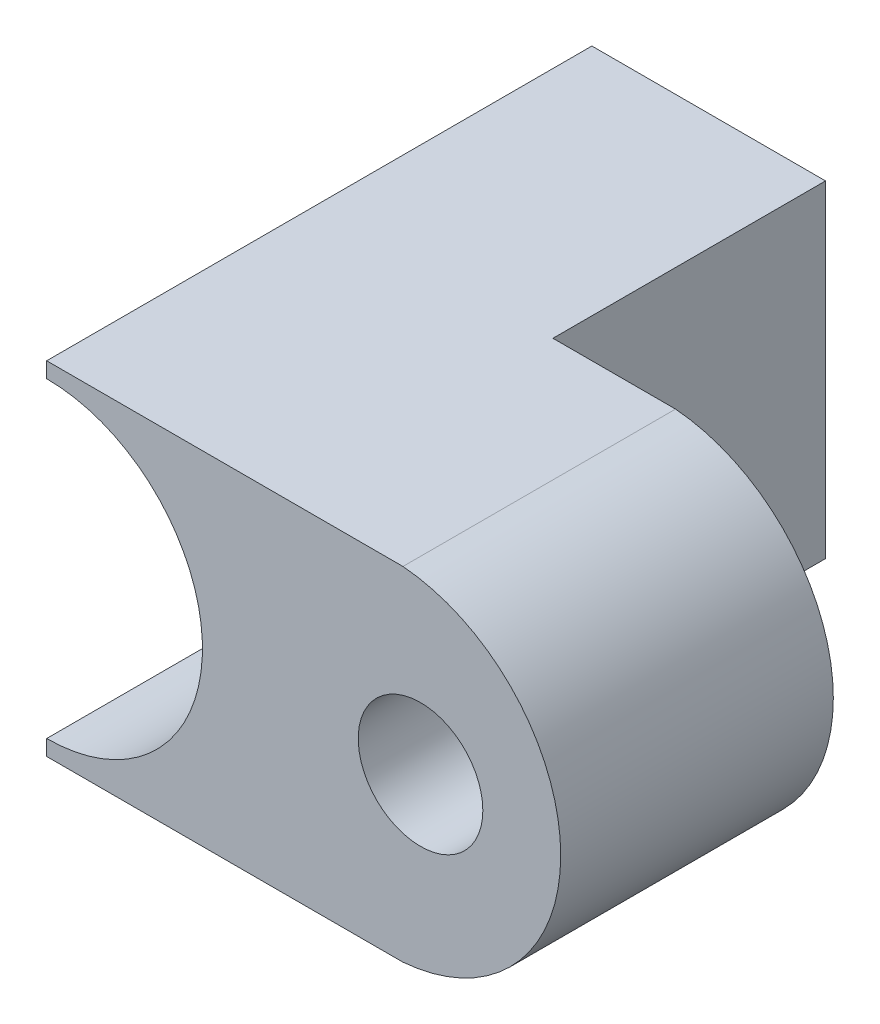
SolidWorks part; units mm, degrees
material "AISI Type A2 Tool Steel Custom"
ref_plane "Front Plane" through (0, 0, 0) normal (0, 0, 1) x (1, 0, 0)
ref_plane "Top Plane" through (0, 0, 0) normal (0, 1, 0) x (1, 0, 0)
ref_plane "Right Plane" through (0, 0, 0) normal (1, 0, 0) x (0, 0, -1)
sketch "Sketch1" plane through (0, 0, 0) normal (0, 0, 1) x (1, 0, 0)
  line L1 (0, -1.27) -> (29.0467, -1.27)
  line L3 (0, 26.67) -> (29.0467, 26.67)
  line L9 (0, 25.4) -> (0, 26.67)
  line L10 (0, 0) -> (0, -1.27)
  arc A1 (0, 0) -> (0, 25.4) centre (0, 12.7) ccw
  arc A4 (29.0467, -1.27) -> (29.0467, 26.67) centre (27.8924, 12.7) ccw
  point P3 (41.91, 12.7)
  dimension "D2" = 25.4
  dimension "D5" = 14.0176
  dimension "D3" = 41.91
  dimension "D1" = 1.27
  dimension "D4" = 1.27
extrude "Boss-Extrude1" add sketch "Sketch1" along normal blind 44.45
sketch "Sketch2" plane through (0, 0, 0) normal (0, 0, -1) x (-1, 0, 0)
  line L0 (-19.05, -1.27) -> (-19.05, 26.67)
  line L1 (0, -1.27) -> (-29.0467, -1.27) construction
  line L2 (-29.0467, 26.67) -> (0, 26.67) construction
  line L3 (0, -1.27) -> (-29.0467, -1.27) construction
  line L4 (-29.0467, 26.67) -> (0, 26.67) construction
  line L5 (-19.05, -1.27) -> (-29.0467, -1.27)
  line L10 (-29.0467, 26.67) -> (-19.05, 26.67)
  arc A1 (-29.0467, 26.67) -> (-29.0467, -1.27) centre (-27.8924, 12.7) ccw construction
  arc A3 (-29.0467, 26.67) -> (-29.0467, -1.27) centre (-27.8924, 12.7) ccw
  dimension "D1" = 19.05
extrude "Cut-Extrude1" cut sketch "Sketch2" against normal blind 22.225
sketch "Sketch3" plane through (0, 0, 44.45) normal (0, 0, 1) x (1, 0, 0)
  arc A0 (29.0467, -1.27) -> (29.0467, 26.67) centre (27.8924, 12.7) ccw construction
  point P0 (30.48, 12.7)
  point P13 (41.91, 12.7)
  dimension "D2" = 11.43
hole_wizard "3/8 (0.375) Diameter Hole1" positions "Sketch3" profile "Sketch4" hole size "3/8" standard "ANSI Inch" end condition through all
sketch "Sketch4" plane through (30.48, 12.7, 44.45) normal (1, 0, 0) x (0, -1, 0)
  line L0 (0, 0) -> (0, 44.45)
  line L1 (0, 44.45) -> (5.08, 44.45)
  line L2 (5.08, 44.45) -> (5.08, 0)
  line L5 (5.08, 0) -> (0, 0)
  line L11 (0, -6.35) -> (0, 107.95) construction
  dimension "Thru Hole Dia." = 10.16
  dimension "Thru Hole Depth" = 44.45
chamfer "Chamfer1" distance 1.27 angle 45 1 edges at (19.05, -1.27, 11.1125)
